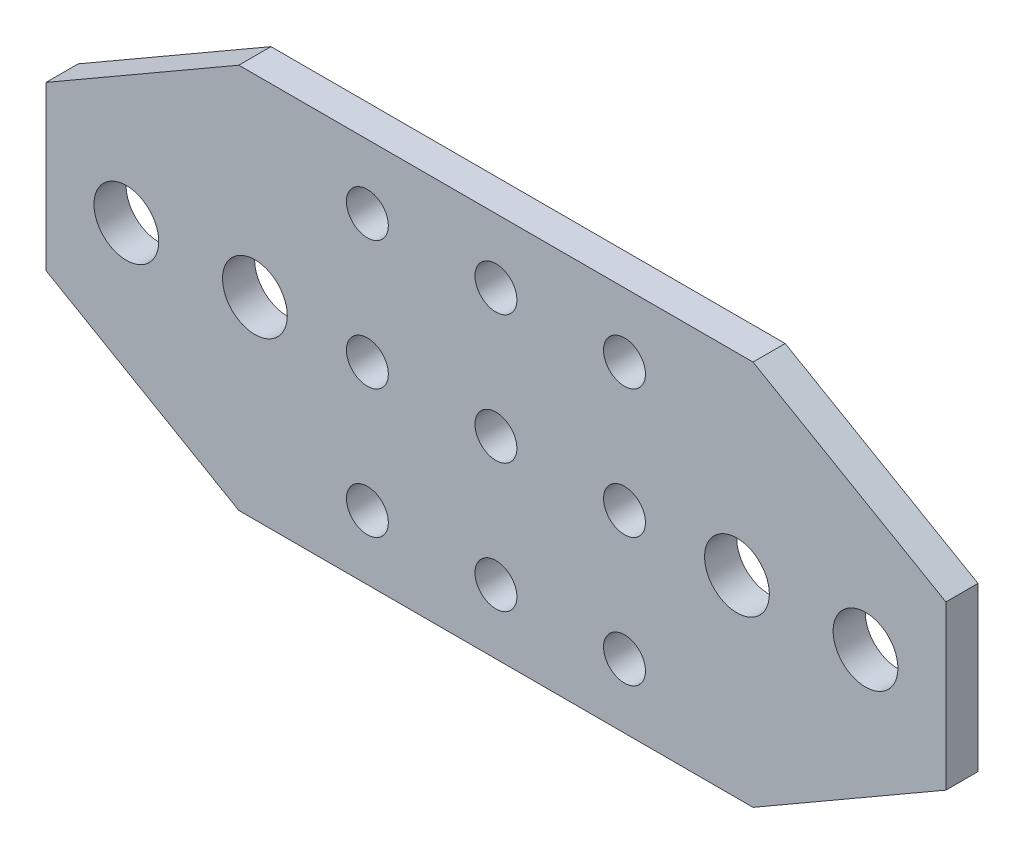
SolidWorks part; units mm, degrees
material "6063-T5"
ref_plane "Front Plane" through (0, 0, 0) normal (0, 0, 1) x (1, 0, 0)
ref_plane "Top Plane" through (0, 0, 0) normal (0, 1, 0) x (1, 0, 0)
ref_plane "Right Plane" through (0, 0, 0) normal (1, 0, 0) x (0, 0, -1)
ref_plane "Plane4" through (0, 0, 0) normal (0, 0, -1) x (-1, 0, 0)
sketch "Sketch1" plane through (0, 0, 0) normal (0, 0, -1) x (-1, 0, 0)
  line L0 (44.45, -8.0515) -> (44.45, 8.0515)
  line L1 (44.45, 8.0515) -> (25.4, 19.05)
  line L2 (25.4, 19.05) -> (-25.4, 19.05)
  line L3 (-25.4, 19.05) -> (-44.45, 8.0515)
  line L4 (-44.45, 8.0515) -> (-44.45, -8.0515)
  line L5 (-44.45, -8.0515) -> (-25.4, -19.05)
  line L6 (-25.4, -19.05) -> (25.4, -19.05)
  line L7 (25.4, -19.05) -> (44.45, -8.0515)
  circle A0 centre (23.8125, 0) radius 3.2004
  circle A1 centre (0, -12.7) radius 2.0701
  circle A2 centre (0, 12.7) radius 2.0701
  circle A3 centre (0, 0) radius 2.0701
  circle A4 centre (36.5125, 0) radius 3.2004
  circle A5 centre (-12.7, -12.7) radius 2.0701
  circle A6 centre (12.7, 12.7) radius 2.0701
  circle A7 centre (12.7, -12.7) radius 2.0701
  circle A8 centre (-12.7, 12.7) radius 2.0701
  circle A9 centre (-36.5125, 0) radius 3.2004
  circle A10 centre (12.7, 0) radius 2.0701
  circle A11 centre (-12.7, 0) radius 2.0701
  circle A12 centre (-23.8125, 0) radius 3.2004
extrude "Boss-Extrude1" add sketch "Sketch1" against normal blind 3.175
